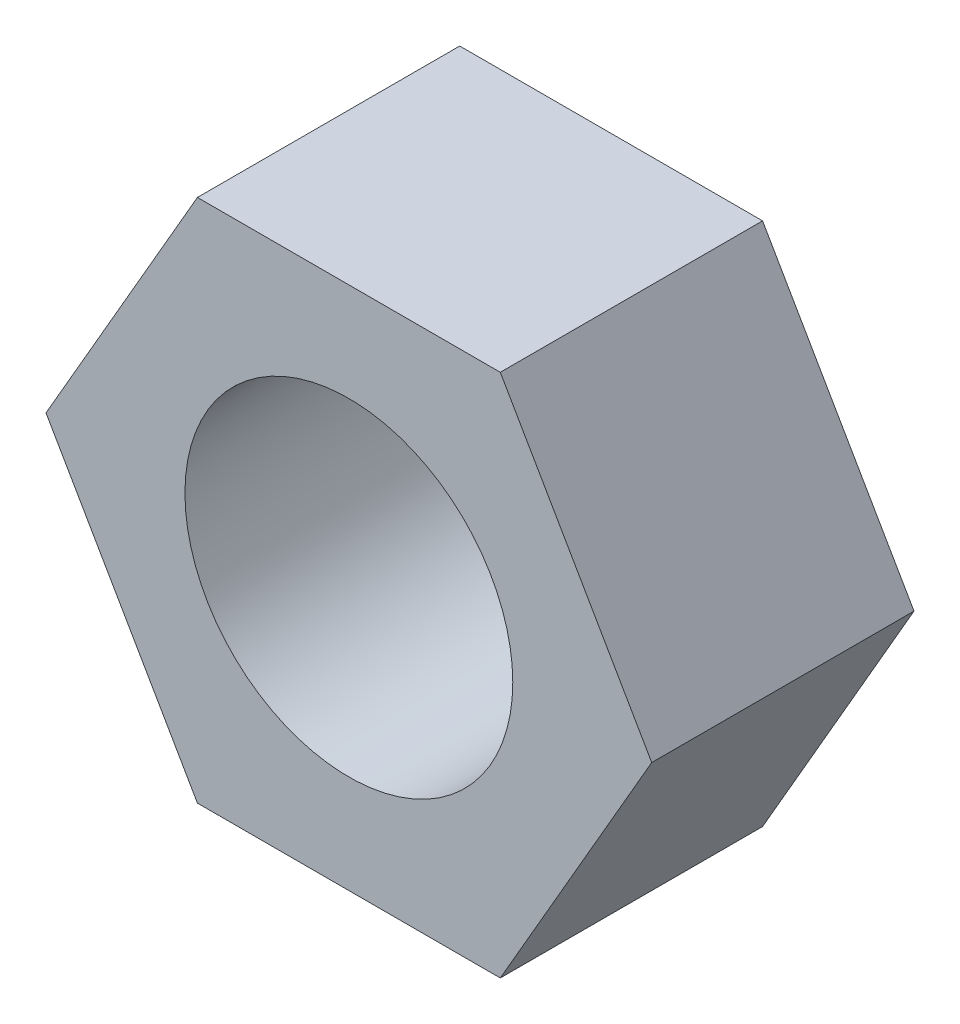
SolidWorks part; units mm, degrees
ref_plane "Plan de face" through (0, 0, 0) normal (0, 0, 1) x (1, 0, 0)
ref_plane "Plan de dessus" through (0, 0, 0) normal (0, 1, 0) x (1, 0, 0)
ref_plane "Plan de droite" through (0, 0, 0) normal (1, 0, 0) x (0, 0, -1)
sketch "Esquisse1" plane through (0, 0, 0) normal (0, 0, 1) x (1, 0, 0)
  line L1 (4.6188, 0) -> (2.3094, 4)
  line L2 (2.3094, 4) -> (-2.3094, 4)
  line L3 (-2.3094, 4) -> (-4.6188, 0)
  line L4 (-4.6188, 0) -> (-2.3094, -4)
  line L5 (-2.3094, -4) -> (2.3094, -4)
  line L6 (2.3094, -4) -> (4.6188, 0)
  circle A0 centre (0, 0) radius 2.5
  circle A1 centre (0, 0) radius 4 construction
  dimension "D1" = 5
  dimension "D2" = 8
extrude "Boss.-Extru.1" add sketch "Esquisse1" along normal blind 4
